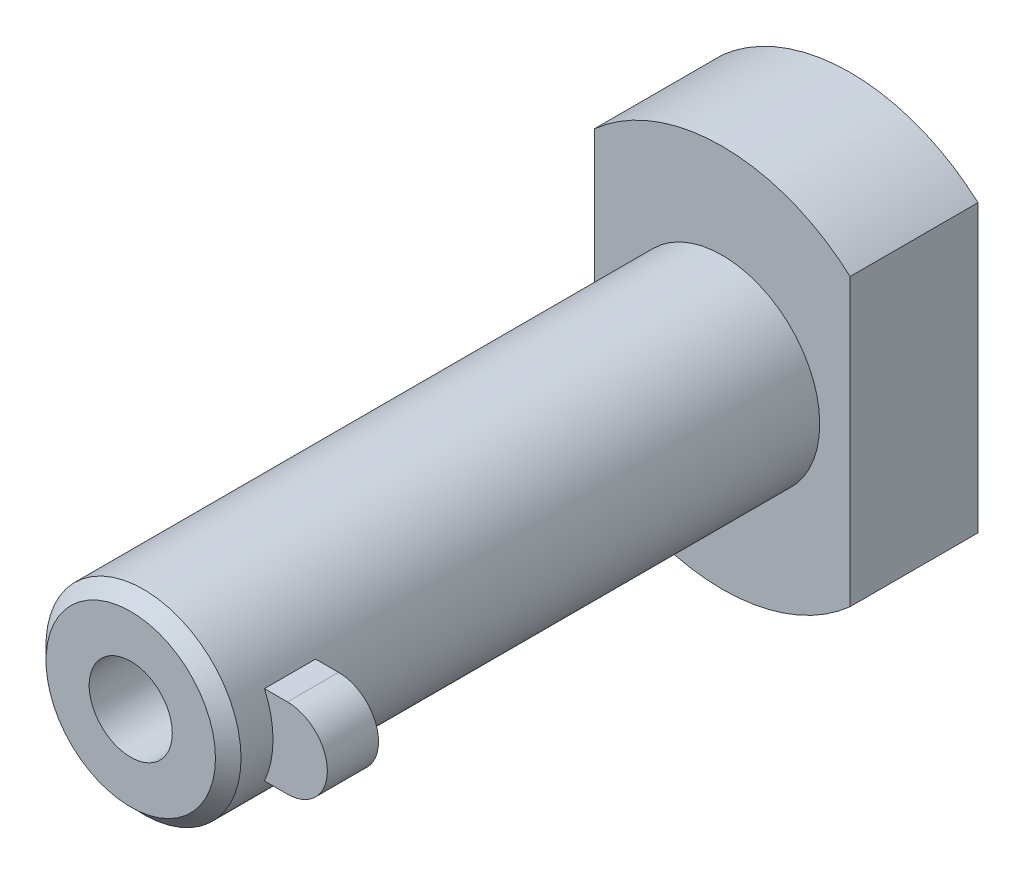
SolidWorks part; units mm, degrees
ref_plane "Ebene vorne" through (0, 0, 0) normal (0, 0, 1) x (1, 0, 0)
ref_plane "Ebene oben" through (0, 0, 0) normal (0, 1, 0) x (1, 0, 0)
ref_plane "Ebene rechts" through (0, 0, 0) normal (1, 0, 0) x (0, 0, -1)
sketch "Skizze1" plane through (0, 0, 0) normal (0, 0, 1) x (1, 0, 0)
  line L0 (-4, -4.4721) -> (-4, 4.4721)
  line L1 (0, 0) -> (0, -6) construction
  line L2 (4, 4.4721) -> (4, -4.4721)
  circle A0 centre (0, 0) radius 6
  dimension "D1" = 12
  dimension "D2" = 8
extrude "Aufsatz-Linear austragen1" add sketch "Skizze1" along normal blind 4
sketch "Skizze2" plane through (0, 0, 4) normal (0, 0, 1) x (1, 0, 0)
  circle A0 centre (0, 0) radius 3.05
  dimension "D1" = 6.1
extrude "Aufsatz-Linear austragen2" add sketch "Skizze2" along normal blind 18.5
sketch "Skizze3" plane through (0, 0, 4) normal (0, 0, 1) x (1, 0, 0)
  line L0 (0, 0) -> (3.5, 0) construction
  line L1 (2.7821, 1.25) -> (3.5, 1.25)
  line L2 (2.7821, -1.25) -> (3.5, -1.25)
  arc A0 (3.5, 1.25) -> (3.5, -1.25) centre (3.5, 0) cw
  circle A1 centre (0, 0) radius 3.05
  circle A2 centre (0, 0) radius 3.05
  dimension "D2" = 3.5
  dimension "D3" = 2.5
  dimension "D1" = 0
extrude "Aufsatz-Linear austragen3" add sketch "Skizze3" along normal blind 1.6 from offset 15.5
sketch "Skizze4" plane through (0, 0, 22.5) normal (0, 0, 1) x (1, 0, 0)
  circle A0 centre (0, 0) radius 1.3
  dimension "D1" = 2.6
extrude "Schnitt-Linear austragen1" cut sketch "Skizze4" against normal up to next
chamfer "Fase1" distance 0.4 angle 45 1 edges at (3.05, 0, 22.5)
